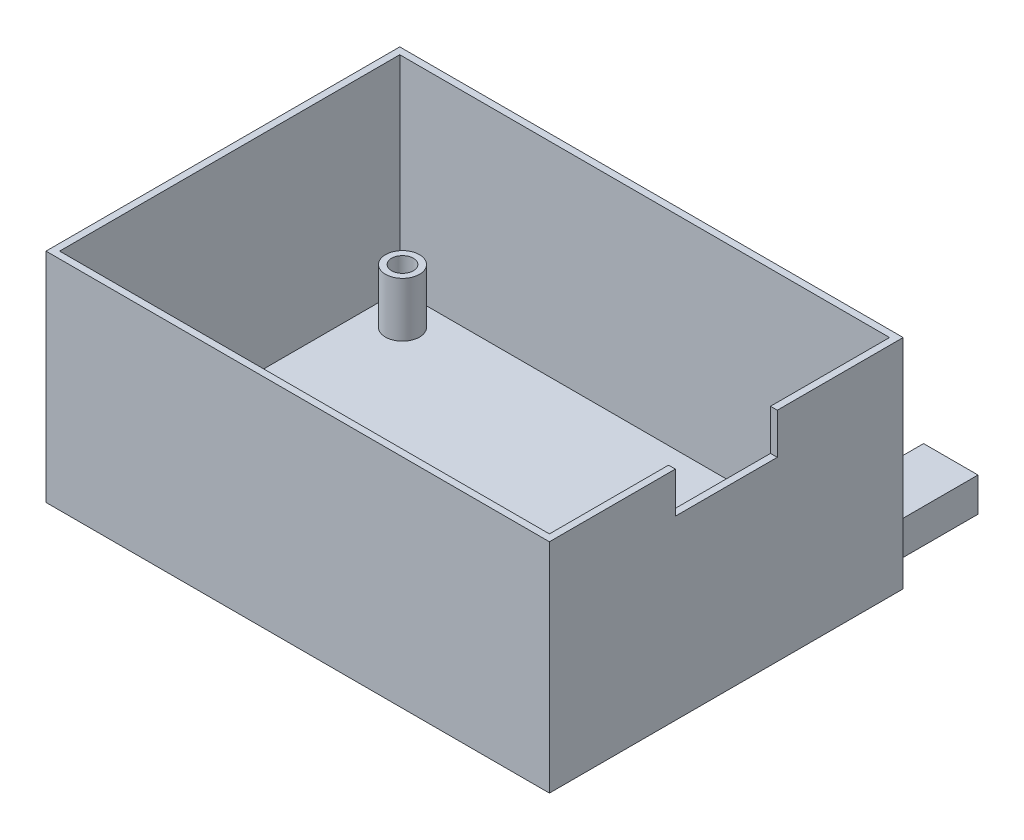
SolidWorks part; units mm, degrees
ref_plane "Front Plane" through (0, 0, 0) normal (0, 0, 1) x (1, 0, 0)
ref_plane "Top Plane" through (0, 0, 0) normal (0, 1, 0) x (1, 0, 0)
ref_plane "Right Plane" through (0, 0, 0) normal (1, 0, 0) x (0, 0, -1)
sketch "Enclosure Shell Sketch" plane through (0, 0, 0) normal (0, 1, 0) x (1, 0, 0)
  line L1 (37, 26) -> (-37, 26)
  line L2 (37, 26) -> (37, -26)
  line L3 (37, -26) -> (-37, -26)
  line L4 (-37, 26) -> (-37, -26)
  line L5 (37, 26) -> (-37, -26) construction
  line L6 (37, -26) -> (-37, 26) construction
  point P0 (0, 0)
  dimension "D1" = 74
  dimension "D2" = 52
extrude "Enclosure Shell Feature" add sketch "Enclosure Shell Sketch" along normal blind 32
sketch "Enclosure Gap Sketch" plane through (0, 32, 0) normal (0, 1, 0) x (1, 0, 0)
  line L1 (-36, 25) -> (36, 25)
  line L2 (-36, 25) -> (-36, -25)
  line L3 (-36, -25) -> (36, -25)
  line L4 (36, 25) -> (36, -25)
  line L5 (-36, 25) -> (36, -25) construction
  line L6 (-36, -25) -> (36, 25) construction
  point P0 (0, 0)
  dimension "D1" = 50
  dimension "D2" = 72
extrude "Enclosure Gap Feature" cut sketch "Enclosure Gap Sketch" against normal blind 30
sketch "Screw Shell Sketch" plane through (0, 2, 0) normal (0, 1, 0) x (1, 0, 0)
  line L6 (37, -26) -> (37, 26) construction
  line L7 (37, 26) -> (-37, 26) construction
  line L8 (-37, -26) -> (37, -26) construction
  circle A0 centre (-31.096, 20.5) radius 2.5
  circle A1 centre (-31.096, -20.5) radius 2.5
  circle A2 centre (31.1, 20.5) radius 2.5
  circle A3 centre (31.1, -20.5) radius 2.5
  dimension "D1" = 62.196
  dimension "D3" = 5.5
  dimension "D5" = 5.9
  dimension "D2" = 5.9
  dimension "D4" = 62.196
  dimension "D6" = 5.5
extrude "Screw Shell Feature" add sketch "Screw Shell Sketch" along normal blind 8
sketch "Screw Hole Sketch" plane through (0, 10, 0) normal (0, 1, 0) x (1, 0, 0)
  circle A0 centre (-31.096, 20.5) radius 1.6
  circle A1 centre (-31.096, -20.5) radius 1.6
  circle A2 centre (31.1, -20.5) radius 1.6
  circle A3 centre (31.1, 20.5) radius 1.6
extrude "Screw Hole Feature" cut sketch "Screw Hole Sketch" against normal blind 8
sketch "Battery Cut Sketch" plane through (37, 0, 0) normal (-1, 0, 0) x (0, 0, 1)
  line L0 (0, 32) -> (7.4925, 32)
  line L1 (-26, 32) -> (26, 32) construction
  line L2 (7.4925, 32) -> (7.4925, 26)
  line L3 (7.4925, 26) -> (-7.5, 26)
  line L4 (-7.5, 26) -> (-7.5, 32)
  line L5 (-7.5, 32) -> (0, 32)
  dimension "D1" = 6
  dimension "D2" = 6
extrude "Battery Cut" cut sketch "Battery Cut Sketch" along normal up to next and the other way through all
sketch "Camera Cord Hole Sketch" plane through (0, 2, 0) normal (0, 1, 0) x (1, 0, 0)
  line L1 (-21, -11) -> (-13, -11)
  line L2 (-21, -11) -> (-21, -15)
  line L3 (-21, -15) -> (-13, -15)
  line L4 (-13, -11) -> (-13, -15)
  line L5 (-21, -11) -> (-13, -15) construction
  line L6 (-21, -15) -> (-13, -11) construction
  line L10 (-36, 25) -> (-36, -25) construction
  line L11 (-36, -25) -> (36, -25) construction
  point P0 (-17, -13)
  dimension "D1" = 4
  dimension "D2" = 8
  dimension "D3" = 19
  dimension "D4" = 10
extrude "Camera Cord Hole" cut sketch "Camera Cord Hole Sketch" against normal through all
sketch "Tab Feature Sketch" plane through (0, 0, -26) normal (0, 0, -1) x (-1, 0, 0)
  line L0 (-37, 0) -> (37, 0) construction
  line L1 (-33, 5) -> (-25, 5)
  line L2 (-33, 5) -> (-33, 0)
  line L3 (-33, 0) -> (-25, 0)
  line L4 (-25, 5) -> (-25, 0)
  line L5 (-33, 5) -> (-25, 0) construction
  line L6 (-33, 0) -> (-25, 5) construction
  line L7 (-37, 32) -> (-37, 0) construction
  line L13 (37, 32) -> (37, 0) construction
  line L14 (25, 5) -> (33, 5)
  line L15 (25, 5) -> (25, 0)
  line L16 (25, 0) -> (33, 0)
  line L17 (33, 5) -> (33, 0)
  line L18 (25, 5) -> (33, 0) construction
  line L19 (25, 0) -> (33, 5) construction
  point P0 (-29, 2.5)
  point P9 (29, 2.5)
  dimension "D1" = 8
  dimension "D2" = 5
  dimension "D3" = 0
  dimension "D4" = 4
  dimension "D5" = 4
  dimension "D6" = 5
  dimension "D7" = 8
extrude "Tab Feature" add sketch "Tab Feature Sketch" along normal blind 15
